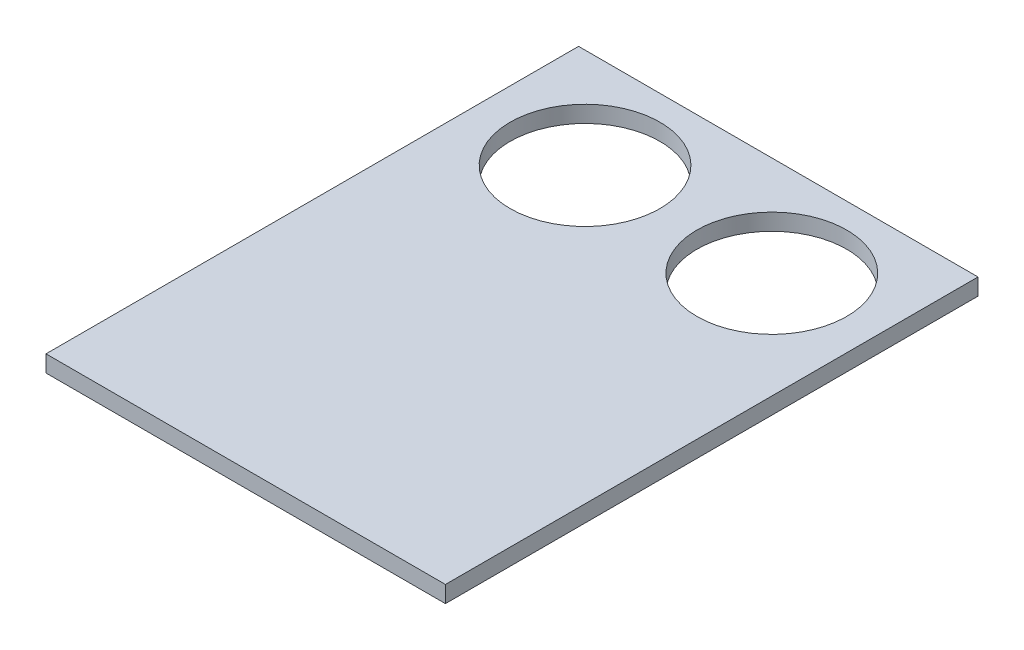
SolidWorks part; units mm, degrees
ref_plane "Front Plane" through (0, 0, 0) normal (0, 0, 1) x (1, 0, 0)
ref_plane "Top Plane" through (0, 0, 0) normal (0, 1, 0) x (1, 0, 0)
ref_plane "Right Plane" through (0, 0, 0) normal (1, 0, 0) x (0, 0, -1)
sketch "Sketch1" plane through (0, 0, 0) normal (0, 1, 0) x (1, 0, 0)
  line L0 (0, -19.05) -> (20.2819, -19.05) construction
  line L1 (0, 0) -> (76.2, 0)
  line L2 (0, 0) -> (0, -101.6)
  line L3 (0, -101.6) -> (76.2, -101.6)
  line L4 (76.2, 0) -> (76.2, -101.6)
  line L5 (27.6142, -19.05) -> (23.9481, -12.7)
  line L6 (23.9481, -12.7) -> (16.6157, -12.7)
  line L7 (16.6157, -12.7) -> (12.9496, -19.05)
  line L8 (12.9496, -19.05) -> (16.6157, -25.4)
  line L9 (16.6157, -25.4) -> (23.9481, -25.4)
  line L10 (23.9481, -25.4) -> (27.6142, -19.05)
  line L11 (55.9181, -11.7177) -> (49.5681, -15.3838)
  line L12 (49.5681, -15.3838) -> (49.5681, -22.7162)
  line L13 (49.5681, -22.7162) -> (55.9181, -26.3823)
  line L14 (55.9181, -26.3823) -> (62.2681, -22.7162)
  line L15 (62.2681, -22.7162) -> (62.2681, -15.3838)
  line L16 (62.2681, -15.3838) -> (55.9181, -11.7177)
  line L17 (20.2819, -19.05) -> (55.9181, -19.05) construction
  line L18 (55.9181, -19.05) -> (76.2, -19.05) construction
  circle A0 centre (20.2819, -19.05) radius 6.35 construction
  circle A1 centre (55.9181, -19.05) radius 6.35 construction
  dimension "D1" = 35.6362
  dimension "D2" = 19.05
  dimension "D3" = 12.7
  dimension "D4" = 12.7
  dimension "D5" = 101.6
  dimension "D6" = 76.2
extrude "Boss-Extrude1" add sketch "Sketch1" along normal blind 3.175
sketch "Sketch2" plane through (0, 3.175, 0) normal (0, 1, 0) x (1, 0, 0)
  line L0 (20.2819, -12.7) -> (20.2819, -25.4) construction
  line L1 (23.9481, -12.7) -> (16.6157, -12.7) construction
  line L2 (16.6157, -25.4) -> (23.9481, -25.4) construction
  line L3 (20.2819, -25.4) -> (49.5681, -19.05) construction
  line L4 (49.5681, -15.3838) -> (49.5681, -22.7162) construction
  line L5 (49.5681, -19.05) -> (62.2681, -19.05) construction
  line L6 (62.2681, -22.7162) -> (62.2681, -15.3838) construction
  circle A0 centre (20.2819, -19.05) radius 14.2875
  circle A1 centre (55.9181, -19.05) radius 14.2875
  dimension "D1" = 28.575
  dimension "D2" = 28.575
extrude "Cut-Extrude1" cut sketch "Sketch2" against normal blind 28.575
